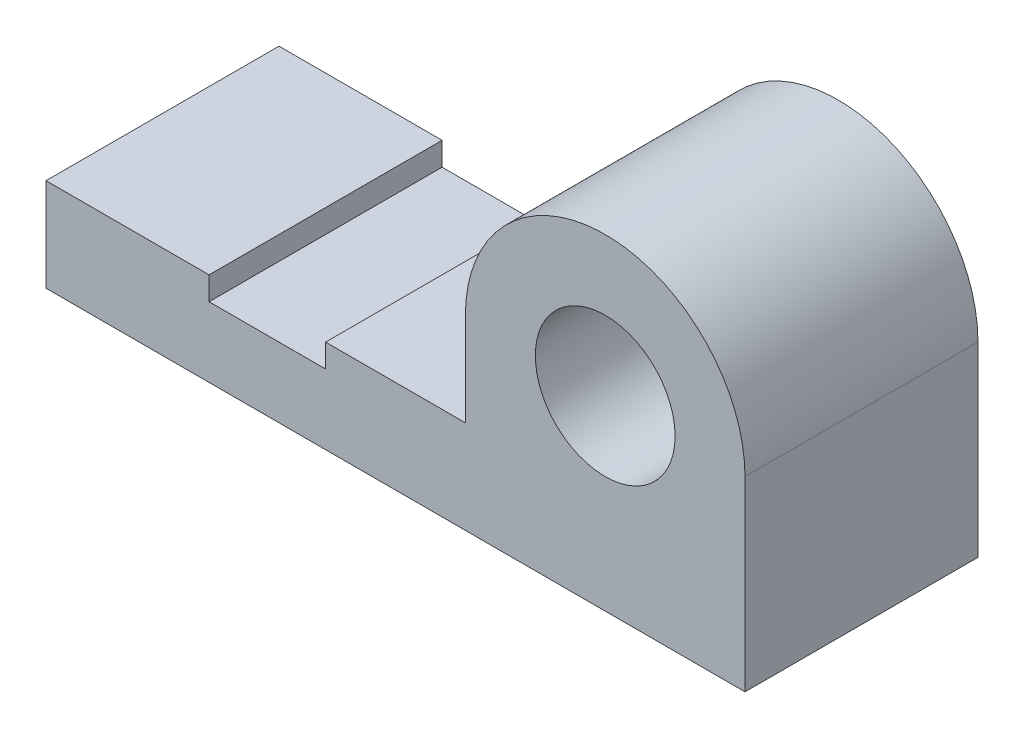
SolidWorks part; units mm, degrees
ref_plane "Front Plane" through (0, 0, 0) normal (0, 0, 1) x (1, 0, 0)
ref_plane "Top Plane" through (0, 0, 0) normal (0, 1, 0) x (1, 0, 0)
ref_plane "Right Plane" through (0, 0, 0) normal (1, 0, 0) x (0, 0, -1)
sketch "Sketch1" plane through (0, 0, 0) normal (0, 0, 1) x (1, 0, 0)
  line L0 (0, 0) -> (-150, 0)
  line L1 (-150, 0) -> (-150, 20)
  line L2 (-150, 20) -> (-115, 20)
  line L3 (-115, 20) -> (-115, 15)
  line L4 (-115, 15) -> (-90, 15)
  line L5 (-90, 15) -> (-90, 20)
  line L6 (-90, 20) -> (-60, 20)
  line L7 (0, 40) -> (0, 0)
  line L8 (-60, 20) -> (-60, 40)
  line L9 (-60, 40) -> (-60, 20)
  arc A1 (-60, 40) -> (0, 40) centre (-30, 40) cw
  circle A2 centre (-30, 40) radius 15
  dimension "D5" = 30
  dimension "D6" = 30
  dimension "D1" = 150
  dimension "D2" = 20
  dimension "D3" = 15
  dimension "D4" = 40
  dimension "D7" = 25
  dimension "D8" = 35
extrude "Boss-Extrude1" add sketch "Sketch1" along normal blind 50 contours A1 L8 L6 L5 L4 L3 L2 L1 L0 L7 A2
